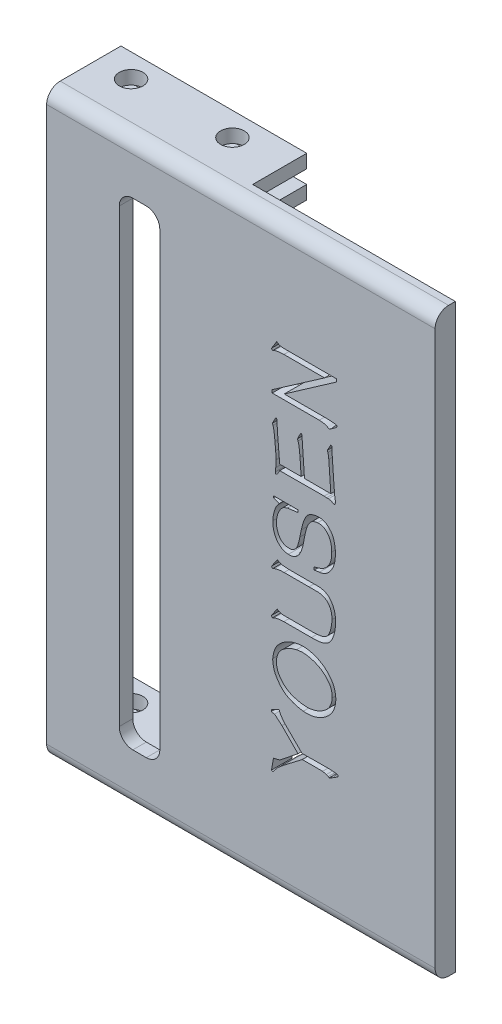
SolidWorks part; units mm, degrees
material "PET"
ref_plane "前视基准面" through (0, 0, 0) normal (0, 0, 1) x (1, 0, 0)
ref_plane "上视基准面" through (0, 0, 0) normal (0, 1, 0) x (1, 0, 0)
ref_plane "右视基准面" through (0, 0, 0) normal (1, 0, 0) x (0, 0, -1)
other "Configuration Table"
sketch "草图1" plane through (0, 0, 0) normal (0, 1, 0) x (1, 0, 0)
  line L1 (-15, 5.5) -> (15, 5.5)
  line L2 (-15, 5.5) -> (-15, -5.5)
  line L3 (-15, -5.5) -> (15, -5.5)
  line L4 (15, 5.5) -> (15, -5.5)
  line L5 (-15, 5.5) -> (15, -5.5) construction
  line L6 (-15, -5.5) -> (15, 5.5) construction
  point P0 (0, 0)
  dimension "D1" = 30
  dimension "D2" = 11
extrude "凸台-拉伸1" add sketch "草图1" along normal blind 6
sketch "草图2" plane through (-15, 0, 0) normal (-1, 0, 0) x (0, 0, 1)
  line L0 (-5.5, 6) -> (-5.5, 0) construction
  line L1 (-13.5, 2) -> (2.5, 2)
  line L2 (-13.5, 2) -> (-13.5, 4)
  line L3 (-13.5, 4) -> (2.5, 4)
  line L4 (2.5, 2) -> (2.5, 4)
  line L5 (-13.5, 2) -> (2.5, 4) construction
  line L6 (-13.5, 4) -> (2.5, 2) construction
  line L7 (-5.5, 6) -> (5.5, 6) construction
  line L8 (5.5, 6) -> (5.5, 0) construction
  point P0 (-5.5, 3)
  dimension "D1" = 2
  dimension "D2" = 3
extrude "切除-拉伸1" cut sketch "草图2" against normal blind 144
sketch "草图3" plane through (0, 6, 0) normal (0, 1, 0) x (1, 0, 0)
  line L0 (2, 5.5) -> (-2, 5.5)
  line L1 (15, 5.5) -> (-15, 5.5) construction
  line L2 (-2, 5.5) -> (-2, -3.5)
  line L3 (-2, -3.5) -> (-15, -3.5)
  line L4 (-15, 5.5) -> (-15, -5.5) construction
  line L5 (-15, -3.5) -> (-15, -5.5)
  line L6 (-15, -5.5) -> (15, -5.5)
  line L7 (-15, -5.5) -> (15, -5.5) construction
  line L8 (0, 5.5) -> (0, -5.5) construction
  line L9 (15, -3.5) -> (15, -5.5)
  line L10 (2, -3.5) -> (15, -3.5)
  line L11 (2, 5.5) -> (2, -3.5)
  dimension "D1" = 2
  dimension "D2" = 2
extrude "凸台-拉伸2" add sketch "草图3" along normal blind 74
sketch "草图4" plane through (0, 6, 0) normal (0, 1, 0) x (1, 0, 0)
  line L0 (-15, 5.5) -> (-15, 2) construction
  line L1 (-15, 5.5) -> (-15, -3.5) construction
  line L2 (-15, 2) -> (15, 2) construction
  line L3 (15, -3.5) -> (15, 5.5) construction
  line L4 (0, 5.5) -> (0, -5.5) construction
  line L5 (2, 5.5) -> (-2, 5.5) construction
  line L6 (-15, -5.5) -> (15, -5.5) construction
  circle A0 centre (-7.5, 2) radius 1.75
  circle A1 centre (7.5, 2) radius 1.75
  point P10 (0, 2)
  dimension "D2" = 7.5
  dimension "D3" = 3.5
  dimension "D1" = 3.5
extrude "切除-拉伸2" cut sketch "草图4" against normal blind 144
sketch "草图5" plane through (-15, 0, 0) normal (-1, 0, 0) x (0, 0, 1)
  line L1 (-5.5, 0) -> (5.5, 0)
  line L2 (-5.5, 0) -> (-5.5, 80)
  line L3 (-5.5, 80) -> (5.5, 80)
  line L4 (5.5, 0) -> (5.5, 80)
extrude "切除-拉伸3" cut sketch "草图5" against normal blind 2.5
sketch "草图6" plane through (0, 6, 0) normal (0, 1, 0) x (1, 0, 0)
  line L0 (-12.5, -2.5) -> (-12.5, 7.5) construction
  line L1 (-22.5, 7.5) -> (-25.5, 7.5)
  line L2 (-12.5, -2.5) -> (-12.5, -5.5)
  arc A0 (-22.5, 7.5) -> (-12.5, -2.5) centre (-12.5, 7.5) ccw
  arc A1 (-25.5, 7.5) -> (-12.5, -5.5) centre (-12.5, 7.5) ccw
  dimension "D1" = 10
sketch "草图7" plane through (0, 80, 0) normal (0, 1, 0) x (1, 0, 0)
  line L1 (-2, 5.5) -> (2, 5.5)
  line L2 (-2, 5.5) -> (-2, -3.5)
  line L3 (-2, -3.5) -> (2, -3.5)
  line L4 (2, 5.5) -> (2, -3.5)
extrude "切除-拉伸4" cut sketch "草图7" against normal up to surface (74 mm away) up to face at (-7.25, 6, -1)
ref_plane "基准面1" through (0, 43, 0) normal (0, 1, 0) x (1, 0, 0)
mirror "镜向1" about plane through (0, 43, 0) normal (0, 1, 0) of "切除-拉伸3", "切除-拉伸2", "切除-拉伸1", "凸台-拉伸1"
sketch "草图8" plane through (15, 0, 0) normal (1, 0, 0) x (0, 0, -1)
  line L0 (-5.5, 86) -> (5.5, 86) construction
  line L1 (-5.5, 0) -> (-2.5, 0)
  line L2 (-5.5, 0) -> (-5.5, 86)
  line L3 (-5.5, 86) -> (-2.5, 86)
  line L4 (-2.5, 0) -> (-2.5, 86)
  line L5 (-2.5, 84) -> (-2.5, 82) construction
  dimension "D1" = 0
extrude "凸台-拉伸3" add sketch "草图8" along normal blind 30
sketch "草图9" plane through (0, 0, 3.5) normal (0, 0, -1) x (-1, 0, 0)
  line L0 (-1.25, 80) -> (-1.25, 6) construction
  line L1 (-15, 80) -> (12.5, 80) construction
  line L2 (-15, 6) -> (12.5, 6) construction
  line L4 (-4.25, 7.6353) -> (1.75, 7.6353)
  line L5 (-4.25, 7.6353) -> (-4.25, 78.3647)
  line L6 (-4.25, 78.3647) -> (1.75, 78.3647)
  line L7 (1.75, 7.6353) -> (1.75, 78.3647)
  line L8 (-4.25, 7.6353) -> (1.75, 78.3647) construction
  line L9 (-4.25, 78.3647) -> (1.75, 7.6353) construction
  point P6 (-1.25, 43)
  dimension "D1" = 6
extrude "切除-拉伸5" cut sketch "草图9" against normal blind 10
fillet "圆角1" radius 2 4 edges at (4.25, 7.6353, 4.5) (-1.75, 7.6353, 4.5) (-1.75, 78.3647, 4.5) (4.25, 78.3647, 4.5)
fillet "圆角2" radius 2 2 edges at (16.25, 86, 5.5) (16.25, 0, 5.5)
sketch "草图10" plane through (0, 0, 5.5) normal (0, 0, 1) x (1, 0, 0)
  text T0 "\r\nYOUSEN" font "汉仪长仿宋体" height 10
extrude "切除-拉伸6" cut sketch "草图10" against normal blind 10
